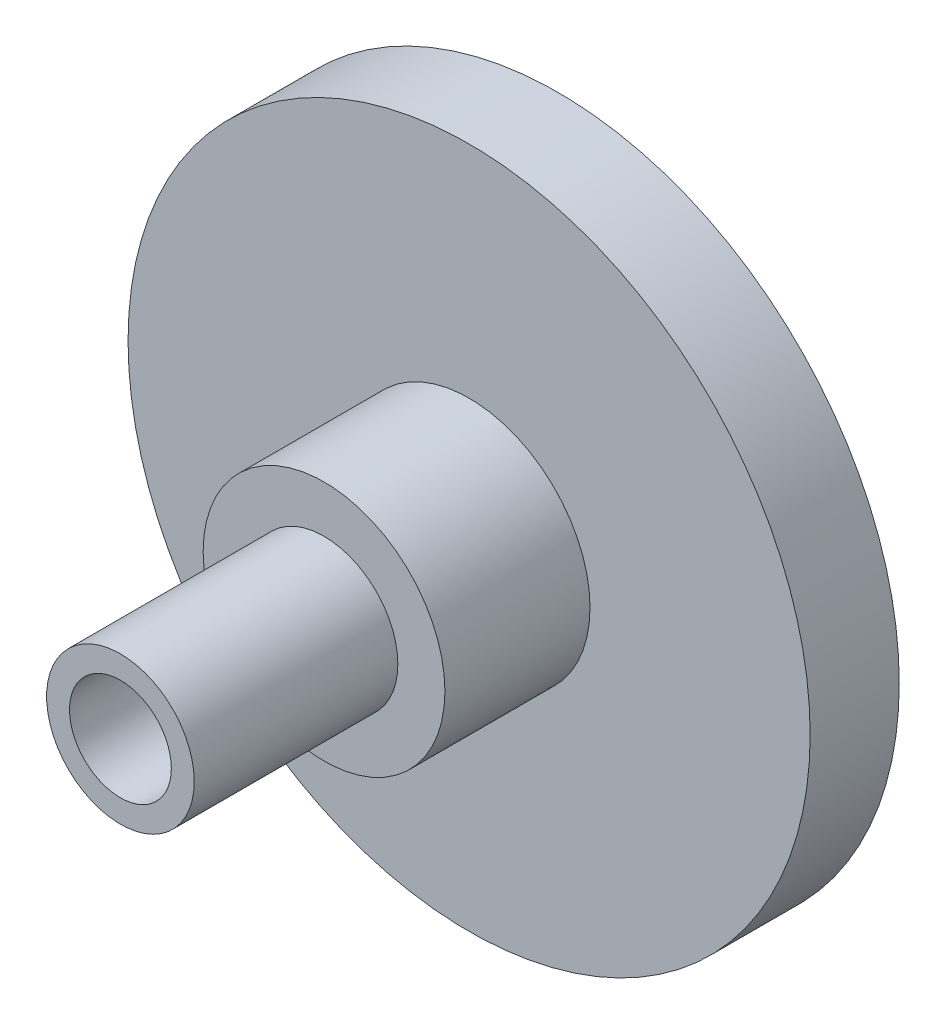
SolidWorks part; units mm, degrees
ref_plane "前视基准面" through (0, 0, 0) normal (0, 0, 1) x (1, 0, 0)
ref_plane "上视基准面" through (0, 0, 0) normal (0, 1, 0) x (1, 0, 0)
ref_plane "右视基准面" through (0, 0, 0) normal (1, 0, 0) x (0, 0, -1)
sketch "草图1" plane through (0, 0, 0) normal (0, 0, 1) x (1, 0, 0)
  circle A0 centre (0, 0) radius 6.7
  circle A1 centre (0, 0) radius 1
  dimension "D1" = 2
  dimension "D2" = 13.4
extrude "凸台-拉伸1" add sketch "草图1" along normal blind 1.75
sketch "草图2" plane through (0, 0, 1.75) normal (0, 0, 1) x (1, 0, 0)
  circle A0 centre (0, 0) radius 1 construction
  circle A1 centre (0, 0) radius 1
  circle A2 centre (0, 0) radius 2.375
  dimension "D1" = 4.75
extrude "凸台-拉伸2" add sketch "草图2" along normal blind 2.85
sketch "草图3" plane through (0, 0, 4.6) normal (0, 0, 1) x (1, 0, 0)
  circle A0 centre (0, 0) radius 1.45
  circle A1 centre (0, 0) radius 1 construction
  circle A2 centre (0, 0) radius 1
  dimension "D1" = 2.9
extrude "凸台-拉伸3" add sketch "草图3" along normal blind 4
